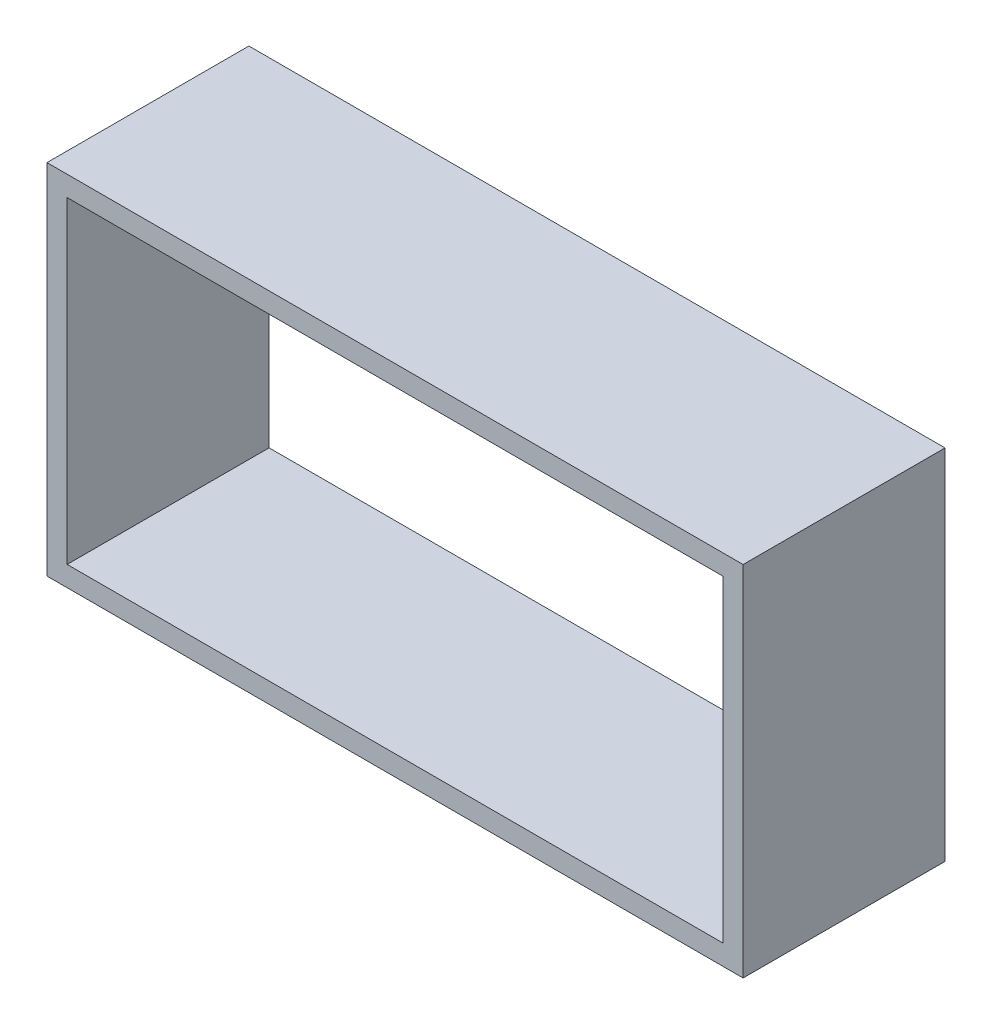
SolidWorks part; units mm, degrees
ref_plane "Front Plane" through (0, 0, 0) normal (0, 0, 1) x (1, 0, 0)
ref_plane "Top Plane" through (0, 0, 0) normal (0, 1, 0) x (1, 0, 0)
ref_plane "Right Plane" through (0, 0, 0) normal (1, 0, 0) x (0, 0, -1)
sketch "Sketch1" plane through (0, 0, 0) normal (0, 0, 1) x (1, 0, 0)
  line L1 (0, 0) -> (87.5635, 0)
  line L2 (0, 0) -> (0, 45.0426)
  line L3 (0, 45.0426) -> (87.5635, 45.0426)
  line L4 (87.5635, 0) -> (87.5635, 45.0426)
extrude "Boss-Extrude1" add sketch "Sketch1" along normal blind 25.4
sketch "Sketch2" plane through (0, 0, 25.4) normal (0, 0, 1) x (1, 0, 0)
  line L8 (2.54, 42.5026) -> (2.54, 2.54)
  line L9 (2.54, 2.54) -> (85.0235, 2.54)
  line L10 (85.0235, 2.54) -> (85.0235, 42.5026)
  line L11 (85.0235, 42.5026) -> (2.54, 42.5026)
  line L12 (2.54, 42.5026) -> (2.54, 2.54)
  line L13 (2.54, 2.54) -> (85.0235, 2.54)
  line L14 (85.0235, 2.54) -> (85.0235, 42.5026)
  line L15 (85.0235, 42.5026) -> (2.54, 42.5026)
  dimension "D1" = 2.54
extrude "Cut-Extrude1" cut sketch "Sketch2" against normal through all
